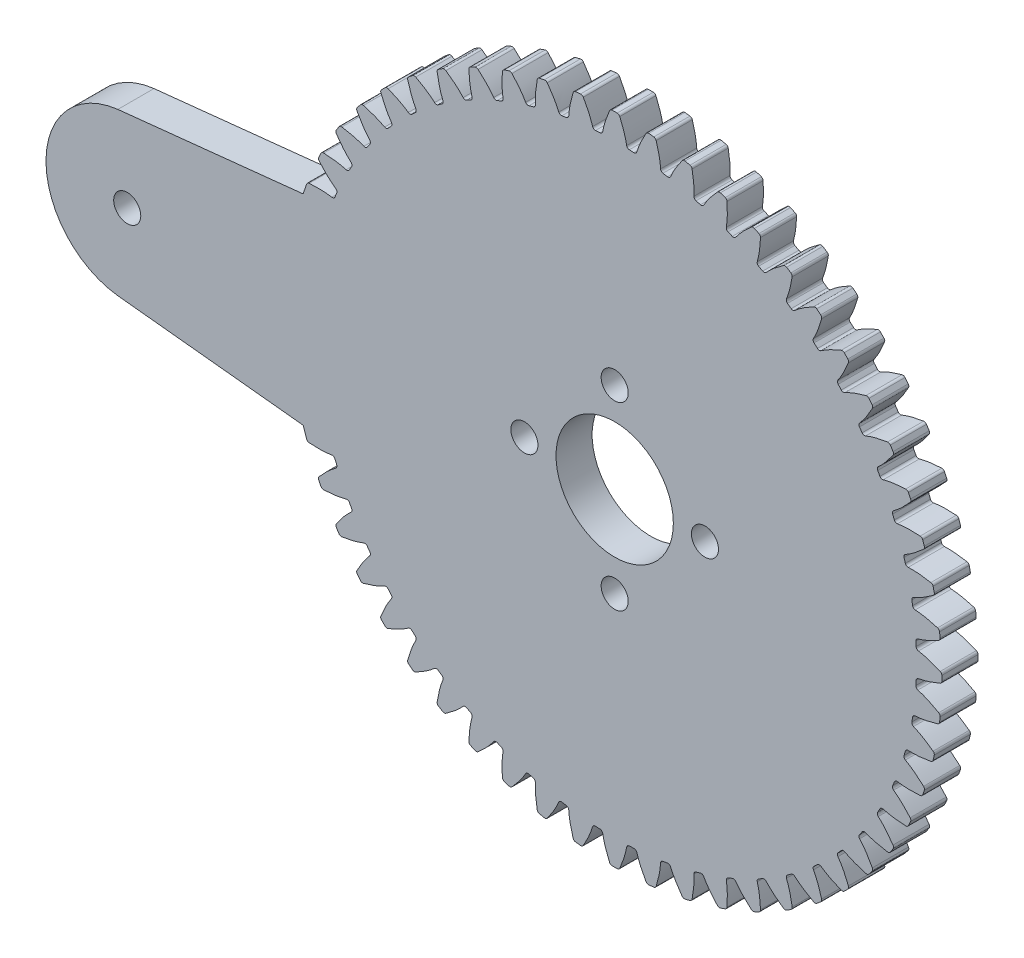
SolidWorks part; units mm, degrees
ref_plane "前视基准面" through (0, 0, 0) normal (0, 0, 1) x (1, 0, 0)
ref_plane "上视基准面" through (0, 0, 0) normal (0, 1, 0) x (1, 0, 0)
ref_plane "右视基准面" through (0, 0, 0) normal (1, 0, 0) x (0, 0, -1)
sketch "草图1" plane through (0, 0, 0) normal (0, 0, 1) x (1, 0, 0)
  line B0 (-34.5094, 11.0978) -> (-55.0401, 8.9397)
  line B1 (-55.0401, -8.9397) -> (-34.5094, -11.0978)
  line B2 (-62.9994, -0.1) -> (-62.9994, 0.1)
  circle B3 centre (10, 0) radius 0.925
  circle B4 centre (0, -10) radius 0.925
  circle B5 centre (0, 10) radius 0.925
  circle B6 centre (-10, 0) radius 0.925
  circle B7 centre (0, 0) radius 6.5
  arc B8 (-34.5094, -11.0978) -> (-34.1217, -12.2382) centre (0, 0) ccw
  circle B9 centre (-54, 0) radius 1.5
  arc B10 (-55.0401, 8.9397) -> (-62.9994, 0.1) centre (-54, 0) ccw
  arc B11 (-62.9994, -0.1) -> (-55.0401, -8.9397) centre (-54, 0) ccw
  arc B12 (-3.7786, 36.0525) -> (-4.3386, 35.9894) centre (0, 0) ccw
  arc B13 (-5.3496, 33.0068) -> (-5.601, 32.9651) centre (0, 0) ccw
  arc B14 (-2.4485, 33.592) -> (-2.1292, 33.3696) centre (-2.1491, 33.6815) ccw
  arc B15 (-5.3496, 33.0068) -> (-5.0878, 33.2946) centre (-5.3996, 33.3153) ccw
  arc B16 (-4.3386, 35.9894) -> (-4.6013, 35.7665) centre (-4.3012, 35.6792) ccw
  arc B17 (-3.4729, 35.8936) -> (-3.7786, 36.0525) centre (-3.746, 35.7417) ccw
  arc B18 (-1.8749, 33.3849) -> (-2.1292, 33.3696) centre (0, 0) ccw
  arc B19 (0.2818, 36.2489) -> (-0.2818, 36.2489) centre (0, 0) ccw
  arc B20 (-1.6204, 33.3982) -> (-1.8749, 33.3849) centre (0, 0) ccw
  arc B21 (1.328, 33.6549) -> (1.6204, 33.3982) centre (1.6355, 33.7103) ccw
  arc B22 (-1.6204, 33.3982) -> (-1.328, 33.6549) centre (-1.6355, 33.7103) ccw
  arc B23 (-0.2818, 36.2489) -> (-0.5677, 36.0568) centre (-0.2793, 35.9364) ccw
  arc B24 (0.5677, 36.0568) -> (0.2818, 36.2489) centre (0.2793, 35.9364) ccw
  arc B25 (1.8749, 33.3849) -> (1.6204, 33.3982) centre (0, 0) ccw
  arc B26 (4.3386, 35.9894) -> (3.7786, 36.0525) centre (0, 0) ccw
  arc B27 (2.1292, 33.3696) -> (1.8749, 33.3849) centre (0, 0) ccw
  arc B28 (5.0878, 33.2946) -> (5.3496, 33.0068) centre (5.3996, 33.3153) ccw
  arc B29 (2.1292, 33.3696) -> (2.4485, 33.592) centre (2.1491, 33.6815) ccw
  arc B30 (3.7786, 36.0525) -> (3.4729, 35.8936) centre (3.746, 35.7417) ccw
  arc B31 (4.6013, 35.7665) -> (4.3386, 35.9894) centre (4.3012, 35.6792) ccw
  arc B32 (5.601, 32.9651) -> (5.3496, 33.0068) centre (0, 0) ccw
  arc B33 (8.3409, 35.2774) -> (7.7914, 35.4028) centre (0, 0) ccw
  arc B34 (5.852, 32.9214) -> (5.601, 32.9651) centre (0, 0) ccw
  arc B35 (8.7836, 32.5156) -> (9.0116, 32.2003) centre (9.0958, 32.5012) ccw
  arc B36 (5.852, 32.9214) -> (6.1942, 33.1066) centre (5.9067, 33.2291) ccw
  arc B37 (7.7914, 35.4028) -> (7.4699, 35.2791) centre (7.7243, 35.0976) ccw
  arc B38 (8.5769, 35.0264) -> (8.3409, 35.2774) centre (8.2689, 34.9733) ccw
  arc B39 (9.2567, 32.1307) -> (9.0116, 32.2003) centre (0, 0) ccw
  arc B40 (12.2382, 34.1217) -> (11.7063, 34.3078) centre (0, 0) ccw
  arc B41 (9.5013, 32.0592) -> (9.2567, 32.1307) centre (0, 0) ccw
  arc B42 (12.369, 31.3277) -> (12.5602, 30.9888) centre (12.6776, 31.2785) ccw
  arc B43 (9.5013, 32.0592) -> (9.862, 32.2049) centre (9.5901, 32.3588) ccw
  arc B44 (11.7063, 34.3078) -> (11.3729, 34.2209) centre (11.6054, 34.012) ccw
  arc B45 (12.4447, 33.8459) -> (12.2382, 34.1217) centre (12.1327, 33.8275) ccw
  arc B46 (12.796, 30.8922) -> (12.5602, 30.9888) centre (0, 0) ccw
  arc B47 (15.9817, 32.5369) -> (15.4739, 32.7814) centre (0, 0) ccw
  arc B48 (13.031, 30.7938) -> (12.796, 30.8922) centre (0, 0) ccw
  arc B49 (15.7988, 29.7458) -> (15.9509, 29.3877) centre (16.0999, 29.6623) ccw
  arc B50 (13.031, 30.7938) -> (13.4058, 30.8982) centre (13.1528, 31.0816) ccw
  arc B51 (15.4739, 32.7814) -> (15.1329, 32.7324) centre (15.3405, 32.4988) ccw
  arc B52 (16.156, 32.2397) -> (15.9817, 32.5369) centre (15.8439, 32.2564) ccw
  arc B53 (16.1744, 29.2653) -> (15.9509, 29.3877) centre (0, 0) ccw
  arc B54 (19.5242, 30.5429) -> (19.047, 30.8427) centre (0, 0) ccw
  arc B55 (16.3969, 29.1412) -> (16.1744, 29.2653) centre (0, 0) ccw
  arc B56 (19.0299, 27.7899) -> (19.1409, 27.417) centre (19.3198, 27.6732) ccw
  arc B57 (16.3969, 29.1412) -> (16.781, 29.2029) centre (16.5501, 29.4135) ccw
  arc B58 (19.047, 30.8427) -> (18.7026, 30.8322) centre (18.8828, 30.5769) ccw
  arc B59 (19.6641, 30.2281) -> (19.5242, 30.5429) centre (19.3559, 30.2796) ccw
  arc B60 (19.3493, 27.2703) -> (19.1409, 27.417) centre (0, 0) ccw
  arc B61 (22.8211, 28.1649) -> (22.3805, 28.5162) centre (0, 0) ccw
  arc B62 (19.5566, 27.1221) -> (19.3493, 27.2703) centre (0, 0) ccw
  arc B63 (22.0218, 25.4845) -> (22.0903, 25.1015) centre (22.2968, 25.3361) ccw
  arc B64 (19.5566, 27.1221) -> (19.9452, 27.1404) centre (19.7393, 27.3756) ccw
  arc B65 (22.3805, 28.5162) -> (22.0371, 28.5443) centre (22.1876, 28.2704) ccw
  arc B66 (22.9249, 27.8363) -> (22.8211, 28.1649) centre (22.6244, 27.9221) ccw
  arc B67 (22.281, 24.9324) -> (22.0903, 25.1015) centre (0, 0) ccw
  arc B68 (25.8311, 25.4326) -> (25.4326, 25.8311) centre (0, 0) ccw
  arc B69 (22.4703, 24.7619) -> (22.281, 24.9324) centre (0, 0) ccw
  arc B70 (24.7366, 22.8586) -> (24.7619, 22.4703) centre (24.9933, 22.6803) ccw
  arc B71 (22.4703, 24.7619) -> (22.8586, 24.7366) centre (22.6803, 24.9933) ccw
  arc B72 (25.4326, 25.8311) -> (25.0945, 25.8974) centre (25.2134, 25.6084) ccw
  arc B73 (25.8974, 25.0945) -> (25.8311, 25.4326) centre (25.6084, 25.2134) ccw
  arc B74 (24.9324, 22.281) -> (24.7619, 22.4703) centre (0, 0) ccw
  arc B75 (28.5162, 22.3805) -> (28.1649, 22.8211) centre (0, 0) ccw
  arc B76 (25.1015, 22.0903) -> (24.9324, 22.281) centre (0, 0) ccw
  arc B77 (27.1404, 19.9452) -> (27.1221, 19.5566) centre (27.3756, 19.7393) ccw
  arc B78 (25.1015, 22.0903) -> (25.4845, 22.0218) centre (25.3361, 22.2968) ccw
  arc B79 (28.1649, 22.8211) -> (27.8363, 22.9249) centre (27.9221, 22.6244) ccw
  arc B80 (28.5443, 22.0371) -> (28.5162, 22.3805) centre (28.2704, 22.1876) ccw
  arc B81 (27.2703, 19.3493) -> (27.1221, 19.5566) centre (0, 0) ccw
  arc B82 (30.8427, 19.047) -> (30.5429, 19.5242) centre (0, 0) ccw
  arc B83 (27.417, 19.1409) -> (27.2703, 19.3493) centre (0, 0) ccw
  arc B84 (29.2029, 16.781) -> (29.1412, 16.3969) centre (29.4135, 16.5501) ccw
  arc B85 (27.417, 19.1409) -> (27.7899, 19.0299) centre (27.6732, 19.3198) ccw
  arc B86 (30.5429, 19.5242) -> (30.2281, 19.6641) centre (30.2796, 19.3559) ccw
  arc B87 (30.8322, 18.7026) -> (30.8427, 19.047) centre (30.5769, 18.8828) ccw
  arc B88 (29.2653, 16.1744) -> (29.1412, 16.3969) centre (0, 0) ccw
  arc B89 (32.7814, 15.4739) -> (32.5369, 15.9817) centre (0, 0) ccw
  arc B90 (29.3877, 15.9509) -> (29.2653, 16.1744) centre (0, 0) ccw
  arc B91 (30.8982, 13.4058) -> (30.7938, 13.031) centre (31.0816, 13.1528) ccw
  arc B92 (29.3877, 15.9509) -> (29.7458, 15.7988) centre (29.6623, 16.0999) ccw
  arc B93 (32.5369, 15.9817) -> (32.2397, 16.156) centre (32.2564, 15.8439) ccw
  arc B94 (32.7324, 15.1329) -> (32.7814, 15.4739) centre (32.4988, 15.3405) ccw
  arc B95 (30.8922, 12.796) -> (30.7938, 13.031) centre (0, 0) ccw
  arc B96 (34.3078, 11.7063) -> (34.1217, 12.2382) centre (0, 0) ccw
  arc B97 (30.9888, 12.5602) -> (30.8922, 12.796) centre (0, 0) ccw
  arc B98 (32.2049, 9.862) -> (32.0592, 9.5013) centre (32.3588, 9.5901) ccw
  arc B99 (30.9888, 12.5602) -> (31.3277, 12.369) centre (31.2785, 12.6776) ccw
  arc B100 (34.1217, 12.2382) -> (33.8459, 12.4447) centre (33.8275, 12.1327) ccw
  arc B101 (34.2209, 11.3729) -> (34.3078, 11.7063) centre (34.012, 11.6054) ccw
  arc B102 (32.1307, 9.2567) -> (32.0592, 9.5013) centre (0, 0) ccw
  arc B103 (35.4028, 7.7914) -> (35.2774, 8.3409) centre (0, 0) ccw
  arc B104 (32.2003, 9.0116) -> (32.1307, 9.2567) centre (0, 0) ccw
  arc B105 (33.1066, 6.1942) -> (32.9214, 5.852) centre (33.2291, 5.9067) ccw
  arc B106 (32.2003, 9.0116) -> (32.5156, 8.7836) centre (32.5012, 9.0958) ccw
  arc B107 (35.2774, 8.3409) -> (35.0264, 8.5769) centre (34.9733, 8.2689) ccw
  arc B108 (35.2791, 7.4699) -> (35.4028, 7.7914) centre (35.0976, 7.7243) ccw
  arc B109 (32.9651, 5.601) -> (32.9214, 5.852) centre (0, 0) ccw
  arc B110 (36.0525, 3.7786) -> (35.9894, 4.3386) centre (0, 0) ccw
  arc B111 (33.0068, 5.3496) -> (32.9651, 5.601) centre (0, 0) ccw
  arc B112 (33.592, 2.4485) -> (33.3696, 2.1292) centre (33.6815, 2.1491) ccw
  arc B113 (33.0068, 5.3496) -> (33.2946, 5.0878) centre (33.3153, 5.3996) ccw
  arc B114 (35.9894, 4.3386) -> (35.7665, 4.6013) centre (35.6792, 4.3012) ccw
  arc B115 (35.8936, 3.4729) -> (36.0525, 3.7786) centre (35.7417, 3.746) ccw
  arc B116 (33.3849, 1.8749) -> (33.3696, 2.1292) centre (0, 0) ccw
  arc B117 (36.2489, -0.2818) -> (36.2489, 0.2818) centre (0, 0) ccw
  arc B118 (33.3982, 1.6204) -> (33.3849, 1.8749) centre (0, 0) ccw
  arc B119 (33.6549, -1.328) -> (33.3982, -1.6204) centre (33.7103, -1.6355) ccw
  arc B120 (33.3982, 1.6204) -> (33.6549, 1.328) centre (33.7103, 1.6355) ccw
  arc B121 (36.2489, 0.2818) -> (36.0568, 0.5677) centre (35.9364, 0.2793) ccw
  arc B122 (36.0568, -0.5677) -> (36.2489, -0.2818) centre (35.9364, -0.2793) ccw
  arc B123 (33.3849, -1.8749) -> (33.3982, -1.6204) centre (0, 0) ccw
  arc B124 (35.9894, -4.3386) -> (36.0525, -3.7786) centre (0, 0) ccw
  arc B125 (33.3696, -2.1292) -> (33.3849, -1.8749) centre (0, 0) ccw
  arc B126 (33.2946, -5.0878) -> (33.0068, -5.3496) centre (33.3153, -5.3996) ccw
  arc B127 (33.3696, -2.1292) -> (33.592, -2.4485) centre (33.6815, -2.1491) ccw
  arc B128 (36.0525, -3.7786) -> (35.8936, -3.4729) centre (35.7417, -3.746) ccw
  arc B129 (35.7665, -4.6013) -> (35.9894, -4.3386) centre (35.6792, -4.3012) ccw
  arc B130 (32.9651, -5.601) -> (33.0068, -5.3496) centre (0, 0) ccw
  arc B131 (35.2774, -8.3409) -> (35.4028, -7.7914) centre (0, 0) ccw
  arc B132 (32.9214, -5.852) -> (32.9651, -5.601) centre (0, 0) ccw
  arc B133 (32.5156, -8.7836) -> (32.2003, -9.0116) centre (32.5012, -9.0958) ccw
  arc B134 (32.9214, -5.852) -> (33.1066, -6.1942) centre (33.2291, -5.9067) ccw
  arc B135 (35.4028, -7.7914) -> (35.2791, -7.4699) centre (35.0976, -7.7243) ccw
  arc B136 (35.0264, -8.5769) -> (35.2774, -8.3409) centre (34.9733, -8.2689) ccw
  arc B137 (32.1307, -9.2567) -> (32.2003, -9.0116) centre (0, 0) ccw
  arc B138 (34.1217, -12.2382) -> (34.3078, -11.7063) centre (0, 0) ccw
  arc B139 (32.0592, -9.5013) -> (32.1307, -9.2567) centre (0, 0) ccw
  arc B140 (31.3277, -12.369) -> (30.9888, -12.5602) centre (31.2785, -12.6776) ccw
  arc B141 (32.0592, -9.5013) -> (32.2049, -9.862) centre (32.3588, -9.5901) ccw
  arc B142 (34.3078, -11.7063) -> (34.2209, -11.3729) centre (34.012, -11.6054) ccw
  arc B143 (33.8459, -12.4447) -> (34.1217, -12.2382) centre (33.8275, -12.1327) ccw
  arc B144 (30.8922, -12.796) -> (30.9888, -12.5602) centre (0, 0) ccw
  arc B145 (32.5369, -15.9817) -> (32.7814, -15.4739) centre (0, 0) ccw
  arc B146 (30.7938, -13.031) -> (30.8922, -12.796) centre (0, 0) ccw
  arc B147 (29.7458, -15.7988) -> (29.3877, -15.9509) centre (29.6623, -16.0999) ccw
  arc B148 (30.7938, -13.031) -> (30.8982, -13.4058) centre (31.0816, -13.1528) ccw
  arc B149 (32.7814, -15.4739) -> (32.7324, -15.1329) centre (32.4988, -15.3405) ccw
  arc B150 (32.2397, -16.156) -> (32.5369, -15.9817) centre (32.2564, -15.8439) ccw
  arc B151 (29.2653, -16.1744) -> (29.3877, -15.9509) centre (0, 0) ccw
  arc B152 (30.5429, -19.5242) -> (30.8427, -19.047) centre (0, 0) ccw
  arc B153 (29.1412, -16.3969) -> (29.2653, -16.1744) centre (0, 0) ccw
  arc B154 (27.7899, -19.0299) -> (27.417, -19.1409) centre (27.6732, -19.3198) ccw
  arc B155 (29.1412, -16.3969) -> (29.2029, -16.781) centre (29.4135, -16.5501) ccw
  arc B156 (30.8427, -19.047) -> (30.8322, -18.7026) centre (30.5769, -18.8828) ccw
  arc B157 (30.2281, -19.6641) -> (30.5429, -19.5242) centre (30.2796, -19.3559) ccw
  arc B158 (27.2703, -19.3493) -> (27.417, -19.1409) centre (0, 0) ccw
  arc B159 (28.1649, -22.8211) -> (28.5162, -22.3805) centre (0, 0) ccw
  arc B160 (27.1221, -19.5566) -> (27.2703, -19.3493) centre (0, 0) ccw
  arc B161 (25.4845, -22.0218) -> (25.1015, -22.0903) centre (25.3361, -22.2968) ccw
  arc B162 (27.1221, -19.5566) -> (27.1404, -19.9452) centre (27.3756, -19.7393) ccw
  arc B163 (28.5162, -22.3805) -> (28.5443, -22.0371) centre (28.2704, -22.1876) ccw
  arc B164 (27.8363, -22.9249) -> (28.1649, -22.8211) centre (27.9221, -22.6244) ccw
  arc B165 (24.9324, -22.281) -> (25.1015, -22.0903) centre (0, 0) ccw
  arc B166 (25.4326, -25.8311) -> (25.8311, -25.4326) centre (0, 0) ccw
  arc B167 (24.7619, -22.4703) -> (24.9324, -22.281) centre (0, 0) ccw
  arc B168 (22.8586, -24.7366) -> (22.4703, -24.7619) centre (22.6803, -24.9933) ccw
  arc B169 (24.7619, -22.4703) -> (24.7366, -22.8586) centre (24.9933, -22.6803) ccw
  arc B170 (25.8311, -25.4326) -> (25.8974, -25.0945) centre (25.6084, -25.2134) ccw
  arc B171 (25.0945, -25.8974) -> (25.4326, -25.8311) centre (25.2134, -25.6084) ccw
  arc B172 (22.281, -24.9324) -> (22.4703, -24.7619) centre (0, 0) ccw
  arc B173 (22.3805, -28.5162) -> (22.8211, -28.1649) centre (0, 0) ccw
  arc B174 (22.0903, -25.1015) -> (22.281, -24.9324) centre (0, 0) ccw
  arc B175 (19.9452, -27.1404) -> (19.5566, -27.1221) centre (19.7393, -27.3756) ccw
  arc B176 (22.0903, -25.1015) -> (22.0218, -25.4845) centre (22.2968, -25.3361) ccw
  arc B177 (22.8211, -28.1649) -> (22.9249, -27.8363) centre (22.6244, -27.9221) ccw
  arc B178 (22.0371, -28.5443) -> (22.3805, -28.5162) centre (22.1876, -28.2704) ccw
  arc B179 (19.3493, -27.2703) -> (19.5566, -27.1221) centre (0, 0) ccw
  arc B180 (19.047, -30.8427) -> (19.5242, -30.5429) centre (0, 0) ccw
  arc B181 (19.1409, -27.417) -> (19.3493, -27.2703) centre (0, 0) ccw
  arc B182 (16.781, -29.2029) -> (16.3969, -29.1412) centre (16.5501, -29.4135) ccw
  arc B183 (19.1409, -27.417) -> (19.0299, -27.7899) centre (19.3198, -27.6732) ccw
  arc B184 (19.5242, -30.5429) -> (19.6641, -30.2281) centre (19.3559, -30.2796) ccw
  arc B185 (18.7026, -30.8322) -> (19.047, -30.8427) centre (18.8828, -30.5769) ccw
  arc B186 (16.1744, -29.2653) -> (16.3969, -29.1412) centre (0, 0) ccw
  arc B187 (15.4739, -32.7814) -> (15.9817, -32.5369) centre (0, 0) ccw
  arc B188 (15.9509, -29.3877) -> (16.1744, -29.2653) centre (0, 0) ccw
  arc B189 (13.4058, -30.8982) -> (13.031, -30.7938) centre (13.1528, -31.0816) ccw
  arc B190 (15.9509, -29.3877) -> (15.7988, -29.7458) centre (16.0999, -29.6623) ccw
  arc B191 (15.9817, -32.5369) -> (16.156, -32.2397) centre (15.8439, -32.2564) ccw
  arc B192 (15.1329, -32.7324) -> (15.4739, -32.7814) centre (15.3405, -32.4988) ccw
  arc B193 (12.796, -30.8922) -> (13.031, -30.7938) centre (0, 0) ccw
  arc B194 (11.7063, -34.3078) -> (12.2382, -34.1217) centre (0, 0) ccw
  arc B195 (12.5602, -30.9888) -> (12.796, -30.8922) centre (0, 0) ccw
  arc B196 (9.862, -32.2049) -> (9.5013, -32.0592) centre (9.5901, -32.3588) ccw
  arc B197 (12.5602, -30.9888) -> (12.369, -31.3277) centre (12.6776, -31.2785) ccw
  arc B198 (12.2382, -34.1217) -> (12.4447, -33.8459) centre (12.1327, -33.8275) ccw
  arc B199 (11.3729, -34.2209) -> (11.7063, -34.3078) centre (11.6054, -34.012) ccw
  arc B200 (9.2567, -32.1307) -> (9.5013, -32.0592) centre (0, 0) ccw
  arc B201 (7.7914, -35.4028) -> (8.3409, -35.2774) centre (0, 0) ccw
  arc B202 (9.0116, -32.2003) -> (9.2567, -32.1307) centre (0, 0) ccw
  arc B203 (6.1942, -33.1066) -> (5.852, -32.9214) centre (5.9067, -33.2291) ccw
  arc B204 (9.0116, -32.2003) -> (8.7836, -32.5156) centre (9.0958, -32.5012) ccw
  arc B205 (8.3409, -35.2774) -> (8.5769, -35.0264) centre (8.2689, -34.9733) ccw
  arc B206 (7.4699, -35.2791) -> (7.7914, -35.4028) centre (7.7243, -35.0976) ccw
  arc B207 (5.601, -32.9651) -> (5.852, -32.9214) centre (0, 0) ccw
  arc B208 (3.7786, -36.0525) -> (4.3386, -35.9894) centre (0, 0) ccw
  arc B209 (5.3496, -33.0068) -> (5.601, -32.9651) centre (0, 0) ccw
  arc B210 (2.4485, -33.592) -> (2.1292, -33.3696) centre (2.1491, -33.6815) ccw
  arc B211 (5.3496, -33.0068) -> (5.0878, -33.2946) centre (5.3996, -33.3153) ccw
  arc B212 (4.3386, -35.9894) -> (4.6013, -35.7665) centre (4.3012, -35.6792) ccw
  arc B213 (3.4729, -35.8936) -> (3.7786, -36.0525) centre (3.746, -35.7417) ccw
  arc B214 (1.8749, -33.3849) -> (2.1292, -33.3696) centre (0, 0) ccw
  arc B215 (-0.2818, -36.2489) -> (0.2818, -36.2489) centre (0, 0) ccw
  arc B216 (1.6204, -33.3982) -> (1.8749, -33.3849) centre (0, 0) ccw
  arc B217 (-1.328, -33.6549) -> (-1.6204, -33.3982) centre (-1.6355, -33.7103) ccw
  arc B218 (1.6204, -33.3982) -> (1.328, -33.6549) centre (1.6355, -33.7103) ccw
  arc B219 (0.2818, -36.2489) -> (0.5677, -36.0568) centre (0.2793, -35.9364) ccw
  arc B220 (-0.5677, -36.0568) -> (-0.2818, -36.2489) centre (-0.2793, -35.9364) ccw
  arc B221 (-1.8749, -33.3849) -> (-1.6204, -33.3982) centre (0, 0) ccw
  arc B222 (-4.3386, -35.9894) -> (-3.7786, -36.0525) centre (0, 0) ccw
  arc B223 (-2.1292, -33.3696) -> (-1.8749, -33.3849) centre (0, 0) ccw
  arc B224 (-5.0878, -33.2946) -> (-5.3496, -33.0068) centre (-5.3996, -33.3153) ccw
  arc B225 (-2.1292, -33.3696) -> (-2.4485, -33.592) centre (-2.1491, -33.6815) ccw
  arc B226 (-3.7786, -36.0525) -> (-3.4729, -35.8936) centre (-3.746, -35.7417) ccw
  arc B227 (-4.6013, -35.7665) -> (-4.3386, -35.9894) centre (-4.3012, -35.6792) ccw
  arc B228 (-5.601, -32.9651) -> (-5.3496, -33.0068) centre (0, 0) ccw
  arc B229 (-8.3409, -35.2774) -> (-7.7914, -35.4028) centre (0, 0) ccw
  arc B230 (-5.852, -32.9214) -> (-5.601, -32.9651) centre (0, 0) ccw
  arc B231 (-8.7836, -32.5156) -> (-9.0116, -32.2003) centre (-9.0958, -32.5012) ccw
  arc B232 (-5.852, -32.9214) -> (-6.1942, -33.1066) centre (-5.9067, -33.2291) ccw
  arc B233 (-7.7914, -35.4028) -> (-7.4699, -35.2791) centre (-7.7243, -35.0976) ccw
  arc B234 (-8.5769, -35.0264) -> (-8.3409, -35.2774) centre (-8.2689, -34.9733) ccw
  arc B235 (-9.2567, -32.1307) -> (-9.0116, -32.2003) centre (0, 0) ccw
  arc B236 (-12.2382, -34.1217) -> (-11.7063, -34.3078) centre (0, 0) ccw
  arc B237 (-9.5013, -32.0592) -> (-9.2567, -32.1307) centre (0, 0) ccw
  arc B238 (-12.369, -31.3277) -> (-12.5602, -30.9888) centre (-12.6776, -31.2785) ccw
  arc B239 (-9.5013, -32.0592) -> (-9.862, -32.2049) centre (-9.5901, -32.3588) ccw
  arc B240 (-11.7063, -34.3078) -> (-11.3729, -34.2209) centre (-11.6054, -34.012) ccw
  arc B241 (-12.4447, -33.8459) -> (-12.2382, -34.1217) centre (-12.1327, -33.8275) ccw
  arc B242 (-12.796, -30.8922) -> (-12.5602, -30.9888) centre (0, 0) ccw
  arc B243 (-15.9817, -32.5369) -> (-15.4739, -32.7814) centre (0, 0) ccw
  arc B244 (-13.031, -30.7938) -> (-12.796, -30.8922) centre (0, 0) ccw
  arc B245 (-15.7988, -29.7458) -> (-15.9509, -29.3877) centre (-16.0999, -29.6623) ccw
  arc B246 (-13.031, -30.7938) -> (-13.4058, -30.8982) centre (-13.1528, -31.0816) ccw
  arc B247 (-15.4739, -32.7814) -> (-15.1329, -32.7324) centre (-15.3405, -32.4988) ccw
  arc B248 (-16.156, -32.2397) -> (-15.9817, -32.5369) centre (-15.8439, -32.2564) ccw
  arc B249 (-16.1744, -29.2653) -> (-15.9509, -29.3877) centre (0, 0) ccw
  arc B250 (-19.5242, -30.5429) -> (-19.047, -30.8427) centre (0, 0) ccw
  arc B251 (-16.3969, -29.1412) -> (-16.1744, -29.2653) centre (0, 0) ccw
  arc B252 (-19.0299, -27.7899) -> (-19.1409, -27.417) centre (-19.3198, -27.6732) ccw
  arc B253 (-16.3969, -29.1412) -> (-16.781, -29.2029) centre (-16.5501, -29.4135) ccw
  arc B254 (-19.047, -30.8427) -> (-18.7026, -30.8322) centre (-18.8828, -30.5769) ccw
  arc B255 (-19.6641, -30.2281) -> (-19.5242, -30.5429) centre (-19.3559, -30.2796) ccw
  arc B256 (-19.3493, -27.2703) -> (-19.1409, -27.417) centre (0, 0) ccw
  arc B257 (-22.8211, -28.1649) -> (-22.3805, -28.5162) centre (0, 0) ccw
  arc B258 (-19.5566, -27.1221) -> (-19.3493, -27.2703) centre (0, 0) ccw
  arc B259 (-22.0218, -25.4845) -> (-22.0903, -25.1015) centre (-22.2968, -25.3361) ccw
  arc B260 (-19.5566, -27.1221) -> (-19.9452, -27.1404) centre (-19.7393, -27.3756) ccw
  arc B261 (-22.3805, -28.5162) -> (-22.0371, -28.5443) centre (-22.1876, -28.2704) ccw
  arc B262 (-22.9249, -27.8363) -> (-22.8211, -28.1649) centre (-22.6244, -27.9221) ccw
  arc B263 (-22.281, -24.9324) -> (-22.0903, -25.1015) centre (0, 0) ccw
  arc B264 (-25.8311, -25.4326) -> (-25.4326, -25.8311) centre (0, 0) ccw
  arc B265 (-22.4703, -24.7619) -> (-22.281, -24.9324) centre (0, 0) ccw
  arc B266 (-24.7366, -22.8586) -> (-24.7619, -22.4703) centre (-24.9933, -22.6803) ccw
  arc B267 (-22.4703, -24.7619) -> (-22.8586, -24.7366) centre (-22.6803, -24.9933) ccw
  arc B268 (-25.4326, -25.8311) -> (-25.0945, -25.8974) centre (-25.2134, -25.6084) ccw
  arc B269 (-25.8974, -25.0945) -> (-25.8311, -25.4326) centre (-25.6084, -25.2134) ccw
  arc B270 (-24.9324, -22.281) -> (-24.7619, -22.4703) centre (0, 0) ccw
  arc B271 (-28.5162, -22.3805) -> (-28.1649, -22.8211) centre (0, 0) ccw
  arc B272 (-25.1015, -22.0903) -> (-24.9324, -22.281) centre (0, 0) ccw
  arc B273 (-27.1404, -19.9452) -> (-27.1221, -19.5566) centre (-27.3756, -19.7393) ccw
  arc B274 (-25.1015, -22.0903) -> (-25.4845, -22.0218) centre (-25.3361, -22.2968) ccw
  arc B275 (-28.1649, -22.8211) -> (-27.8363, -22.9249) centre (-27.9221, -22.6244) ccw
  arc B276 (-28.5443, -22.0371) -> (-28.5162, -22.3805) centre (-28.2704, -22.1876) ccw
  arc B277 (-27.2703, -19.3493) -> (-27.1221, -19.5566) centre (0, 0) ccw
  arc B278 (-30.8427, -19.047) -> (-30.5429, -19.5242) centre (0, 0) ccw
  arc B279 (-27.417, -19.1409) -> (-27.2703, -19.3493) centre (0, 0) ccw
  arc B280 (-29.2029, -16.781) -> (-29.1412, -16.3969) centre (-29.4135, -16.5501) ccw
  arc B281 (-27.417, -19.1409) -> (-27.7899, -19.0299) centre (-27.6732, -19.3198) ccw
  arc B282 (-30.5429, -19.5242) -> (-30.2281, -19.6641) centre (-30.2796, -19.3559) ccw
  arc B283 (-30.8322, -18.7026) -> (-30.8427, -19.047) centre (-30.5769, -18.8828) ccw
  arc B284 (-29.2653, -16.1744) -> (-29.1412, -16.3969) centre (0, 0) ccw
  arc B285 (-32.7814, -15.4739) -> (-32.5369, -15.9817) centre (0, 0) ccw
  arc B286 (-29.3877, -15.9509) -> (-29.2653, -16.1744) centre (0, 0) ccw
  arc B287 (-30.8982, -13.4058) -> (-30.7938, -13.031) centre (-31.0816, -13.1528) ccw
  arc B288 (-29.3877, -15.9509) -> (-29.7458, -15.7988) centre (-29.6623, -16.0999) ccw
  arc B289 (-32.5369, -15.9817) -> (-32.2397, -16.156) centre (-32.2564, -15.8439) ccw
  arc B290 (-32.7324, -15.1329) -> (-32.7814, -15.4739) centre (-32.4988, -15.3405) ccw
  arc B291 (-30.8922, -12.796) -> (-30.7938, -13.031) centre (0, 0) ccw
  arc B292 (-34.3078, -11.7063) -> (-34.1217, -12.2382) centre (0, 0) ccw
  arc B293 (-30.9888, -12.5602) -> (-30.8922, -12.796) centre (0, 0) ccw
  arc B294 (-30.9888, -12.5602) -> (-31.3277, -12.369) centre (-31.2785, -12.6776) ccw
  arc B295 (-34.1217, -12.2382) -> (-33.8459, -12.4447) centre (-33.8275, -12.1327) ccw
  arc B296 (-34.1217, 12.2382) -> (-34.5094, 11.0978) centre (0, 0) ccw
  arc B297 (-31.3277, 12.369) -> (-30.9888, 12.5602) centre (-31.2785, 12.6776) ccw
  arc B298 (-33.8459, 12.4447) -> (-34.1217, 12.2382) centre (-33.8275, 12.1327) ccw
  arc B299 (-30.8922, 12.796) -> (-30.9888, 12.5602) centre (0, 0) ccw
  arc B300 (-32.5369, 15.9817) -> (-32.7814, 15.4739) centre (0, 0) ccw
  arc B301 (-30.7938, 13.031) -> (-30.8922, 12.796) centre (0, 0) ccw
  arc B302 (-29.7458, 15.7988) -> (-29.3877, 15.9509) centre (-29.6623, 16.0999) ccw
  arc B303 (-30.7938, 13.031) -> (-30.8982, 13.4058) centre (-31.0816, 13.1528) ccw
  arc B304 (-32.7814, 15.4739) -> (-32.7324, 15.1329) centre (-32.4988, 15.3405) ccw
  arc B305 (-32.2397, 16.156) -> (-32.5369, 15.9817) centre (-32.2564, 15.8439) ccw
  arc B306 (-29.2653, 16.1744) -> (-29.3877, 15.9509) centre (0, 0) ccw
  arc B307 (-30.5429, 19.5242) -> (-30.8427, 19.047) centre (0, 0) ccw
  arc B308 (-29.1412, 16.3969) -> (-29.2653, 16.1744) centre (0, 0) ccw
  arc B309 (-27.7899, 19.0299) -> (-27.417, 19.1409) centre (-27.6732, 19.3198) ccw
  arc B310 (-29.1412, 16.3969) -> (-29.2029, 16.781) centre (-29.4135, 16.5501) ccw
  arc B311 (-30.8427, 19.047) -> (-30.8322, 18.7026) centre (-30.5769, 18.8828) ccw
  arc B312 (-30.2281, 19.6641) -> (-30.5429, 19.5242) centre (-30.2796, 19.3559) ccw
  arc B313 (-27.2703, 19.3493) -> (-27.417, 19.1409) centre (0, 0) ccw
  arc B314 (-28.1649, 22.8211) -> (-28.5162, 22.3805) centre (0, 0) ccw
  arc B315 (-27.1221, 19.5566) -> (-27.2703, 19.3493) centre (0, 0) ccw
  arc B316 (-25.4845, 22.0218) -> (-25.1015, 22.0903) centre (-25.3361, 22.2968) ccw
  arc B317 (-27.1221, 19.5566) -> (-27.1404, 19.9452) centre (-27.3756, 19.7393) ccw
  arc B318 (-28.5162, 22.3805) -> (-28.5443, 22.0371) centre (-28.2704, 22.1876) ccw
  arc B319 (-27.8363, 22.9249) -> (-28.1649, 22.8211) centre (-27.9221, 22.6244) ccw
  arc B320 (-24.9324, 22.281) -> (-25.1015, 22.0903) centre (0, 0) ccw
  arc B321 (-25.4326, 25.8311) -> (-25.8311, 25.4326) centre (0, 0) ccw
  arc B322 (-24.7619, 22.4703) -> (-24.9324, 22.281) centre (0, 0) ccw
  arc B323 (-22.8586, 24.7366) -> (-22.4703, 24.7619) centre (-22.6803, 24.9933) ccw
  arc B324 (-24.7619, 22.4703) -> (-24.7366, 22.8586) centre (-24.9933, 22.6803) ccw
  arc B325 (-25.8311, 25.4326) -> (-25.8974, 25.0945) centre (-25.6084, 25.2134) ccw
  arc B326 (-25.0945, 25.8974) -> (-25.4326, 25.8311) centre (-25.2134, 25.6084) ccw
  arc B327 (-22.281, 24.9324) -> (-22.4703, 24.7619) centre (0, 0) ccw
  arc B328 (-22.3805, 28.5162) -> (-22.8211, 28.1649) centre (0, 0) ccw
  arc B329 (-22.0903, 25.1015) -> (-22.281, 24.9324) centre (0, 0) ccw
  arc B330 (-19.9452, 27.1404) -> (-19.5566, 27.1221) centre (-19.7393, 27.3756) ccw
  arc B331 (-22.0903, 25.1015) -> (-22.0218, 25.4845) centre (-22.2968, 25.3361) ccw
  arc B332 (-22.8211, 28.1649) -> (-22.9249, 27.8363) centre (-22.6244, 27.9221) ccw
  arc B333 (-22.0371, 28.5443) -> (-22.3805, 28.5162) centre (-22.1876, 28.2704) ccw
  arc B334 (-19.3493, 27.2703) -> (-19.5566, 27.1221) centre (0, 0) ccw
  arc B335 (-19.047, 30.8427) -> (-19.5242, 30.5429) centre (0, 0) ccw
  arc B336 (-19.1409, 27.417) -> (-19.3493, 27.2703) centre (0, 0) ccw
  arc B337 (-16.781, 29.2029) -> (-16.3969, 29.1412) centre (-16.5501, 29.4135) ccw
  arc B338 (-19.1409, 27.417) -> (-19.0299, 27.7899) centre (-19.3198, 27.6732) ccw
  arc B339 (-19.5242, 30.5429) -> (-19.6641, 30.2281) centre (-19.3559, 30.2796) ccw
  arc B340 (-18.7026, 30.8322) -> (-19.047, 30.8427) centre (-18.8828, 30.5769) ccw
  arc B341 (-16.1744, 29.2653) -> (-16.3969, 29.1412) centre (0, 0) ccw
  arc B342 (-15.4739, 32.7814) -> (-15.9817, 32.5369) centre (0, 0) ccw
  arc B343 (-15.9509, 29.3877) -> (-16.1744, 29.2653) centre (0, 0) ccw
  arc B344 (-13.4058, 30.8982) -> (-13.031, 30.7938) centre (-13.1528, 31.0816) ccw
  arc B345 (-15.9509, 29.3877) -> (-15.7988, 29.7458) centre (-16.0999, 29.6623) ccw
  arc B346 (-15.9817, 32.5369) -> (-16.156, 32.2397) centre (-15.8439, 32.2564) ccw
  arc B347 (-15.1329, 32.7324) -> (-15.4739, 32.7814) centre (-15.3405, 32.4988) ccw
  arc B348 (-12.796, 30.8922) -> (-13.031, 30.7938) centre (0, 0) ccw
  arc B349 (-11.7063, 34.3078) -> (-12.2382, 34.1217) centre (0, 0) ccw
  arc B350 (-12.5602, 30.9888) -> (-12.796, 30.8922) centre (0, 0) ccw
  arc B351 (-9.862, 32.2049) -> (-9.5013, 32.0592) centre (-9.5901, 32.3588) ccw
  arc B352 (-12.5602, 30.9888) -> (-12.369, 31.3277) centre (-12.6776, 31.2785) ccw
  arc B353 (-12.2382, 34.1217) -> (-12.4447, 33.8459) centre (-12.1327, 33.8275) ccw
  arc B354 (-11.3729, 34.2209) -> (-11.7063, 34.3078) centre (-11.6054, 34.012) ccw
  arc B355 (-9.2567, 32.1307) -> (-9.5013, 32.0592) centre (0, 0) ccw
  arc B356 (-5.601, 32.9651) -> (-5.852, 32.9214) centre (0, 0) ccw
  arc B357 (-7.4699, 35.2791) -> (-7.7914, 35.4028) centre (-7.7243, 35.0976) ccw
  arc B358 (-8.3409, 35.2774) -> (-8.5769, 35.0264) centre (-8.2689, 34.9733) ccw
  arc B359 (-9.0116, 32.2003) -> (-8.7836, 32.5156) centre (-9.0958, 32.5012) ccw
  arc B360 (-6.1942, 33.1066) -> (-5.852, 32.9214) centre (-5.9067, 33.2291) ccw
  arc B361 (-9.0116, 32.2003) -> (-9.2567, 32.1307) centre (0, 0) ccw
  arc B362 (-7.7914, 35.4028) -> (-8.3409, 35.2774) centre (0, 0) ccw
  spline B363 degree 3 poles (-4.6013, 35.7665) (-4.7005, 35.4253) (-4.8862, 34.766) (-5.031, 33.9352) (-5.0774, 33.451) (-5.0878, 33.2946) knots 0.205794 0.205794 0.205794 0.205794 1.271237 2.259978 2.73007 2.73007 2.73007 2.73007
  spline B364 degree 3 poles (-3.4729, 35.8936) (-3.3002, 35.583) (-2.9725, 34.9816) (-2.6465, 34.2038) (-2.4934, 33.7421) (-2.4485, 33.592) knots 0.205794 0.205794 0.205794 0.205794 1.271237 2.259978 2.73007 2.73007 2.73007 2.73007
  spline B365 degree 3 poles (-0.5677, 36.0568) (-0.7046, 35.7288) (-0.9629, 35.0945) (-1.1998, 34.2851) (-1.3002, 33.8091) (-1.328, 33.6549) knots 0.205794 0.205794 0.205794 0.205794 1.271237 2.259978 2.73007 2.73007 2.73007 2.73007
  spline B366 degree 3 poles (0.5677, 36.0568) (0.7046, 35.7288) (0.9629, 35.0945) (1.1998, 34.2851) (1.3002, 33.8091) (1.328, 33.6549) knots 0.205794 0.205794 0.205794 0.205794 1.271237 2.259978 2.73007 2.73007 2.73007 2.73007
  spline B367 degree 3 poles (3.4729, 35.8936) (3.3002, 35.583) (2.9725, 34.9816) (2.6465, 34.2038) (2.4934, 33.7421) (2.4485, 33.592) knots 0.205794 0.205794 0.205794 0.205794 1.271237 2.259978 2.73007 2.73007 2.73007 2.73007
  spline B368 degree 3 poles (4.6013, 35.7665) (4.7005, 35.4253) (4.8862, 34.766) (5.031, 33.9352) (5.0774, 33.451) (5.0878, 33.2946) knots 0.205794 0.205794 0.205794 0.205794 1.271237 2.259978 2.73007 2.73007 2.73007 2.73007
  spline B369 degree 3 poles (7.4699, 35.2791) (7.2635, 34.9898) (6.8705, 34.4288) (6.4594, 33.6925) (6.2557, 33.2508) (6.1942, 33.1066) knots 0.205794 0.205794 0.205794 0.205794 1.271237 2.259978 2.73007 2.73007 2.73007 2.73007
  spline B370 degree 3 poles (8.5769, 35.0264) (8.6373, 34.6762) (8.748, 34.0003) (8.7989, 33.1585) (8.7908, 32.6722) (8.7836, 32.5156) knots 0.205794 0.205794 0.205794 0.205794 1.271237 2.259978 2.73007 2.73007 2.73007 2.73007
  spline B371 degree 3 poles (11.3729, 34.2209) (11.1354, 33.9565) (10.6821, 33.4431) (10.1912, 32.7574) (9.9392, 32.3413) (9.862, 32.2049) knots 0.205794 0.205794 0.205794 0.205794 1.271237 2.259978 2.73007 2.73007 2.73007 2.73007
  spline B372 degree 3 poles (12.4447, 33.8459) (12.4655, 33.4911) (12.4999, 32.8071) (12.4561, 31.9648) (12.3937, 31.4825) (12.369, 31.3277) knots 0.205794 0.205794 0.205794 0.205794 1.271237 2.259978 2.73007 2.73007 2.73007 2.73007
  spline B373 degree 3 poles (15.1329, 32.7324) (14.8673, 32.4963) (14.3594, 32.0368) (13.7948, 31.4104) (13.4978, 31.0251) (13.4058, 30.8982) knots 0.205794 0.205794 0.205794 0.205794 1.271237 2.259978 2.73007 2.73007 2.73007 2.73007
  spline B374 degree 3 poles (16.156, 32.2397) (16.137, 31.8848) (16.0945, 31.2012) (15.9567, 30.3692) (15.8407, 29.8969) (15.7988, 29.7458) knots 0.205794 0.205794 0.205794 0.205794 1.271237 2.259978 2.73007 2.73007 2.73007 2.73007
  spline B375 degree 3 poles (18.7026, 30.8322) (18.4123, 30.6273) (17.8561, 30.2276) (17.2249, 29.6683) (16.8867, 29.3188) (16.781, 29.2029) knots 0.205794 0.205794 0.205794 0.205794 1.271237 2.259978 2.73007 2.73007 2.73007 2.73007
  spline B376 degree 3 poles (19.6641, 30.2281) (19.6055, 29.8776) (19.4867, 29.203) (19.2567, 28.3917) (19.0884, 27.9353) (19.0299, 27.7899) knots 0.205794 0.205794 0.205794 0.205794 1.271237 2.259978 2.73007 2.73007 2.73007 2.73007
  spline B377 degree 3 poles (22.0371, 28.5443) (21.7257, 28.3732) (21.1282, 28.0383) (20.4384, 27.5532) (20.0631, 27.2437) (19.9452, 27.1404) knots 0.205794 0.205794 0.205794 0.205794 1.271237 2.259978 2.73007 2.73007 2.73007 2.73007
  spline B378 degree 3 poles (22.9249, 27.8363) (22.8274, 27.4946) (22.6339, 26.8376) (22.3144, 26.0571) (22.0962, 25.6224) (22.0218, 25.4845) knots 0.205794 0.205794 0.205794 0.205794 1.271237 2.259978 2.73007 2.73007 2.73007 2.73007
  spline B379 degree 3 poles (25.0945, 25.8974) (24.7659, 25.7623) (24.1346, 25.4964) (23.3948, 25.0916) (22.9873, 24.826) (22.8586, 24.7366) knots 0.205794 0.205794 0.205794 0.205794 1.271237 2.259978 2.73007 2.73007 2.73007 2.73007
  spline B380 degree 3 poles (25.8974, 25.0945) (25.7623, 24.7659) (25.4964, 24.1346) (25.0916, 23.3948) (24.826, 22.9873) (24.7366, 22.8586) knots 0.205794 0.205794 0.205794 0.205794 1.271237 2.259978 2.73007 2.73007 2.73007 2.73007
  spline B381 degree 3 poles (27.8363, 22.9249) (27.4946, 22.8274) (26.8376, 22.6339) (26.0571, 22.3144) (25.6224, 22.0962) (25.4845, 22.0218) knots 0.205794 0.205794 0.205794 0.205794 1.271237 2.259978 2.73007 2.73007 2.73007 2.73007
  spline B382 degree 3 poles (28.5443, 22.0371) (28.3732, 21.7257) (28.0383, 21.1282) (27.5532, 20.4384) (27.2437, 20.0631) (27.1404, 19.9452) knots 0.205794 0.205794 0.205794 0.205794 1.271237 2.259978 2.73007 2.73007 2.73007 2.73007
  spline B383 degree 3 poles (30.2281, 19.6641) (29.8776, 19.6055) (29.203, 19.4867) (28.3917, 19.2567) (27.9353, 19.0884) (27.7899, 19.0299) knots 0.205794 0.205794 0.205794 0.205794 1.271237 2.259978 2.73007 2.73007 2.73007 2.73007
  spline B384 degree 3 poles (30.8322, 18.7026) (30.6273, 18.4123) (30.2276, 17.8561) (29.6683, 17.2249) (29.3188, 16.8867) (29.2029, 16.781) knots 0.205794 0.205794 0.205794 0.205794 1.271237 2.259978 2.73007 2.73007 2.73007 2.73007
  spline B385 degree 3 poles (32.2397, 16.156) (31.8848, 16.137) (31.2012, 16.0945) (30.3692, 15.9567) (29.8969, 15.8407) (29.7458, 15.7988) knots 0.205794 0.205794 0.205794 0.205794 1.271237 2.259978 2.73007 2.73007 2.73007 2.73007
  spline B386 degree 3 poles (32.7324, 15.1329) (32.4963, 14.8673) (32.0368, 14.3594) (31.4104, 13.7948) (31.0251, 13.4978) (30.8982, 13.4058) knots 0.205794 0.205794 0.205794 0.205794 1.271237 2.259978 2.73007 2.73007 2.73007 2.73007
  spline B387 degree 3 poles (33.8459, 12.4447) (33.4911, 12.4655) (32.8071, 12.4999) (31.9648, 12.4561) (31.4825, 12.3937) (31.3277, 12.369) knots 0.205794 0.205794 0.205794 0.205794 1.271237 2.259978 2.73007 2.73007 2.73007 2.73007
  spline B388 degree 3 poles (34.2209, 11.3729) (33.9565, 11.1354) (33.4431, 10.6821) (32.7574, 10.1912) (32.3413, 9.9392) (32.2049, 9.862) knots 0.205794 0.205794 0.205794 0.205794 1.271237 2.259978 2.73007 2.73007 2.73007 2.73007
  spline B389 degree 3 poles (35.0264, 8.5769) (34.6762, 8.6373) (34.0003, 8.748) (33.1585, 8.7989) (32.6722, 8.7908) (32.5156, 8.7836) knots 0.205794 0.205794 0.205794 0.205794 1.271237 2.259978 2.73007 2.73007 2.73007 2.73007
  spline B390 degree 3 poles (35.2791, 7.4699) (34.9898, 7.2635) (34.4288, 6.8705) (33.6925, 6.4594) (33.2508, 6.2557) (33.1066, 6.1942) knots 0.205794 0.205794 0.205794 0.205794 1.271237 2.259978 2.73007 2.73007 2.73007 2.73007
  spline B391 degree 3 poles (35.7665, 4.6013) (35.4253, 4.7005) (34.766, 4.8862) (33.9352, 5.031) (33.451, 5.0774) (33.2946, 5.0878) knots 0.205794 0.205794 0.205794 0.205794 1.271237 2.259978 2.73007 2.73007 2.73007 2.73007
  spline B392 degree 3 poles (35.8936, 3.4729) (35.583, 3.3002) (34.9816, 2.9725) (34.2038, 2.6465) (33.7421, 2.4934) (33.592, 2.4485) knots 0.205794 0.205794 0.205794 0.205794 1.271237 2.259978 2.73007 2.73007 2.73007 2.73007
  spline B393 degree 3 poles (36.0568, 0.5677) (35.7288, 0.7046) (35.0945, 0.9629) (34.2851, 1.1998) (33.8091, 1.3002) (33.6549, 1.328) knots 0.205794 0.205794 0.205794 0.205794 1.271237 2.259978 2.73007 2.73007 2.73007 2.73007
  spline B394 degree 3 poles (36.0568, -0.5677) (35.7288, -0.7046) (35.0945, -0.9629) (34.2851, -1.1998) (33.8091, -1.3002) (33.6549, -1.328) knots 0.205794 0.205794 0.205794 0.205794 1.271237 2.259978 2.73007 2.73007 2.73007 2.73007
  spline B395 degree 3 poles (35.8936, -3.4729) (35.583, -3.3002) (34.9816, -2.9725) (34.2038, -2.6465) (33.7421, -2.4934) (33.592, -2.4485) knots 0.205794 0.205794 0.205794 0.205794 1.271237 2.259978 2.73007 2.73007 2.73007 2.73007
  spline B396 degree 3 poles (35.7665, -4.6013) (35.4253, -4.7005) (34.766, -4.8862) (33.9352, -5.031) (33.451, -5.0774) (33.2946, -5.0878) knots 0.205794 0.205794 0.205794 0.205794 1.271237 2.259978 2.73007 2.73007 2.73007 2.73007
  spline B397 degree 3 poles (35.2791, -7.4699) (34.9898, -7.2635) (34.4288, -6.8705) (33.6925, -6.4594) (33.2508, -6.2557) (33.1066, -6.1942) knots 0.205794 0.205794 0.205794 0.205794 1.271237 2.259978 2.73007 2.73007 2.73007 2.73007
  spline B398 degree 3 poles (35.0264, -8.5769) (34.6762, -8.6373) (34.0003, -8.748) (33.1585, -8.7989) (32.6722, -8.7908) (32.5156, -8.7836) knots 0.205794 0.205794 0.205794 0.205794 1.271237 2.259978 2.73007 2.73007 2.73007 2.73007
  spline B399 degree 3 poles (34.2209, -11.3729) (33.9565, -11.1354) (33.4431, -10.6821) (32.7574, -10.1912) (32.3413, -9.9392) (32.2049, -9.862) knots 0.205794 0.205794 0.205794 0.205794 1.271237 2.259978 2.73007 2.73007 2.73007 2.73007
  spline B400 degree 3 poles (33.8459, -12.4447) (33.4911, -12.4655) (32.8071, -12.4999) (31.9648, -12.4561) (31.4825, -12.3937) (31.3277, -12.369) knots 0.205794 0.205794 0.205794 0.205794 1.271237 2.259978 2.73007 2.73007 2.73007 2.73007
  spline B401 degree 3 poles (32.7324, -15.1329) (32.4963, -14.8673) (32.0368, -14.3594) (31.4104, -13.7948) (31.0251, -13.4978) (30.8982, -13.4058) knots 0.205794 0.205794 0.205794 0.205794 1.271237 2.259978 2.73007 2.73007 2.73007 2.73007
  spline B402 degree 3 poles (32.2397, -16.156) (31.8848, -16.137) (31.2012, -16.0945) (30.3692, -15.9567) (29.8969, -15.8407) (29.7458, -15.7988) knots 0.205794 0.205794 0.205794 0.205794 1.271237 2.259978 2.73007 2.73007 2.73007 2.73007
  spline B403 degree 3 poles (30.8322, -18.7026) (30.6273, -18.4123) (30.2276, -17.8561) (29.6683, -17.2249) (29.3188, -16.8867) (29.2029, -16.781) knots 0.205794 0.205794 0.205794 0.205794 1.271237 2.259978 2.73007 2.73007 2.73007 2.73007
  spline B404 degree 3 poles (30.2281, -19.6641) (29.8776, -19.6055) (29.203, -19.4867) (28.3917, -19.2567) (27.9353, -19.0884) (27.7899, -19.0299) knots 0.205794 0.205794 0.205794 0.205794 1.271237 2.259978 2.73007 2.73007 2.73007 2.73007
  spline B405 degree 3 poles (28.5443, -22.0371) (28.3732, -21.7257) (28.0383, -21.1282) (27.5532, -20.4384) (27.2437, -20.0631) (27.1404, -19.9452) knots 0.205794 0.205794 0.205794 0.205794 1.271237 2.259978 2.73007 2.73007 2.73007 2.73007
  spline B406 degree 3 poles (27.8363, -22.9249) (27.4946, -22.8274) (26.8376, -22.6339) (26.0571, -22.3144) (25.6224, -22.0962) (25.4845, -22.0218) knots 0.205794 0.205794 0.205794 0.205794 1.271237 2.259978 2.73007 2.73007 2.73007 2.73007
  spline B407 degree 3 poles (25.8974, -25.0945) (25.7623, -24.7659) (25.4964, -24.1346) (25.0916, -23.3948) (24.826, -22.9873) (24.7366, -22.8586) knots 0.205794 0.205794 0.205794 0.205794 1.271237 2.259978 2.73007 2.73007 2.73007 2.73007
  spline B408 degree 3 poles (25.0945, -25.8974) (24.7659, -25.7623) (24.1346, -25.4964) (23.3948, -25.0916) (22.9873, -24.826) (22.8586, -24.7366) knots 0.205794 0.205794 0.205794 0.205794 1.271237 2.259978 2.73007 2.73007 2.73007 2.73007
  spline B409 degree 3 poles (22.9249, -27.8363) (22.8274, -27.4946) (22.6339, -26.8376) (22.3144, -26.0571) (22.0962, -25.6224) (22.0218, -25.4845) knots 0.205794 0.205794 0.205794 0.205794 1.271237 2.259978 2.73007 2.73007 2.73007 2.73007
  spline B410 degree 3 poles (22.0371, -28.5443) (21.7257, -28.3732) (21.1282, -28.0383) (20.4384, -27.5532) (20.0631, -27.2437) (19.9452, -27.1404) knots 0.205794 0.205794 0.205794 0.205794 1.271237 2.259978 2.73007 2.73007 2.73007 2.73007
  spline B411 degree 3 poles (19.6641, -30.2281) (19.6055, -29.8776) (19.4867, -29.203) (19.2567, -28.3917) (19.0884, -27.9353) (19.0299, -27.7899) knots 0.205794 0.205794 0.205794 0.205794 1.271237 2.259978 2.73007 2.73007 2.73007 2.73007
  spline B412 degree 3 poles (18.7026, -30.8322) (18.4123, -30.6273) (17.8561, -30.2276) (17.2249, -29.6683) (16.8867, -29.3188) (16.781, -29.2029) knots 0.205794 0.205794 0.205794 0.205794 1.271237 2.259978 2.73007 2.73007 2.73007 2.73007
  spline B413 degree 3 poles (16.156, -32.2397) (16.137, -31.8848) (16.0945, -31.2012) (15.9567, -30.3692) (15.8407, -29.8969) (15.7988, -29.7458) knots 0.205794 0.205794 0.205794 0.205794 1.271237 2.259978 2.73007 2.73007 2.73007 2.73007
  spline B414 degree 3 poles (15.1329, -32.7324) (14.8673, -32.4963) (14.3594, -32.0368) (13.7948, -31.4104) (13.4978, -31.0251) (13.4058, -30.8982) knots 0.205794 0.205794 0.205794 0.205794 1.271237 2.259978 2.73007 2.73007 2.73007 2.73007
  spline B415 degree 3 poles (12.4447, -33.8459) (12.4655, -33.4911) (12.4999, -32.8071) (12.4561, -31.9648) (12.3937, -31.4825) (12.369, -31.3277) knots 0.205794 0.205794 0.205794 0.205794 1.271237 2.259978 2.73007 2.73007 2.73007 2.73007
  spline B416 degree 3 poles (11.3729, -34.2209) (11.1354, -33.9565) (10.6821, -33.4431) (10.1912, -32.7574) (9.9392, -32.3413) (9.862, -32.2049) knots 0.205794 0.205794 0.205794 0.205794 1.271237 2.259978 2.73007 2.73007 2.73007 2.73007
  spline B417 degree 3 poles (8.5769, -35.0264) (8.6373, -34.6762) (8.748, -34.0003) (8.7989, -33.1585) (8.7908, -32.6722) (8.7836, -32.5156) knots 0.205794 0.205794 0.205794 0.205794 1.271237 2.259978 2.73007 2.73007 2.73007 2.73007
  spline B418 degree 3 poles (7.4699, -35.2791) (7.2635, -34.9898) (6.8705, -34.4288) (6.4594, -33.6925) (6.2557, -33.2508) (6.1942, -33.1066) knots 0.205794 0.205794 0.205794 0.205794 1.271237 2.259978 2.73007 2.73007 2.73007 2.73007
  spline B419 degree 3 poles (4.6013, -35.7665) (4.7005, -35.4253) (4.8862, -34.766) (5.031, -33.9352) (5.0774, -33.451) (5.0878, -33.2946) knots 0.205794 0.205794 0.205794 0.205794 1.271237 2.259978 2.73007 2.73007 2.73007 2.73007
  spline B420 degree 3 poles (3.4729, -35.8936) (3.3002, -35.583) (2.9725, -34.9816) (2.6465, -34.2038) (2.4934, -33.7421) (2.4485, -33.592) knots 0.205794 0.205794 0.205794 0.205794 1.271237 2.259978 2.73007 2.73007 2.73007 2.73007
  spline B421 degree 3 poles (0.5677, -36.0568) (0.7046, -35.7288) (0.9629, -35.0945) (1.1998, -34.2851) (1.3002, -33.8091) (1.328, -33.6549) knots 0.205794 0.205794 0.205794 0.205794 1.271237 2.259978 2.73007 2.73007 2.73007 2.73007
  spline B422 degree 3 poles (-0.5677, -36.0568) (-0.7046, -35.7288) (-0.9629, -35.0945) (-1.1998, -34.2851) (-1.3002, -33.8091) (-1.328, -33.6549) knots 0.205794 0.205794 0.205794 0.205794 1.271237 2.259978 2.73007 2.73007 2.73007 2.73007
  spline B423 degree 3 poles (-3.4729, -35.8936) (-3.3002, -35.583) (-2.9725, -34.9816) (-2.6465, -34.2038) (-2.4934, -33.7421) (-2.4485, -33.592) knots 0.205794 0.205794 0.205794 0.205794 1.271237 2.259978 2.73007 2.73007 2.73007 2.73007
  spline B424 degree 3 poles (-4.6013, -35.7665) (-4.7005, -35.4253) (-4.8862, -34.766) (-5.031, -33.9352) (-5.0774, -33.451) (-5.0878, -33.2946) knots 0.205794 0.205794 0.205794 0.205794 1.271237 2.259978 2.73007 2.73007 2.73007 2.73007
  spline B425 degree 3 poles (-7.4699, -35.2791) (-7.2635, -34.9898) (-6.8705, -34.4288) (-6.4594, -33.6925) (-6.2557, -33.2508) (-6.1942, -33.1066) knots 0.205794 0.205794 0.205794 0.205794 1.271237 2.259978 2.73007 2.73007 2.73007 2.73007
  spline B426 degree 3 poles (-8.5769, -35.0264) (-8.6373, -34.6762) (-8.748, -34.0003) (-8.7989, -33.1585) (-8.7908, -32.6722) (-8.7836, -32.5156) knots 0.205794 0.205794 0.205794 0.205794 1.271237 2.259978 2.73007 2.73007 2.73007 2.73007
  spline B427 degree 3 poles (-11.3729, -34.2209) (-11.1354, -33.9565) (-10.6821, -33.4431) (-10.1912, -32.7574) (-9.9392, -32.3413) (-9.862, -32.2049) knots 0.205794 0.205794 0.205794 0.205794 1.271237 2.259978 2.73007 2.73007 2.73007 2.73007
  spline B428 degree 3 poles (-12.4447, -33.8459) (-12.4655, -33.4911) (-12.4999, -32.8071) (-12.4561, -31.9648) (-12.3937, -31.4825) (-12.369, -31.3277) knots 0.205794 0.205794 0.205794 0.205794 1.271237 2.259978 2.73007 2.73007 2.73007 2.73007
  spline B429 degree 3 poles (-15.1329, -32.7324) (-14.8673, -32.4963) (-14.3594, -32.0368) (-13.7948, -31.4104) (-13.4978, -31.0251) (-13.4058, -30.8982) knots 0.205794 0.205794 0.205794 0.205794 1.271237 2.259978 2.73007 2.73007 2.73007 2.73007
  spline B430 degree 3 poles (-16.156, -32.2397) (-16.137, -31.8848) (-16.0945, -31.2012) (-15.9567, -30.3692) (-15.8407, -29.8969) (-15.7988, -29.7458) knots 0.205794 0.205794 0.205794 0.205794 1.271237 2.259978 2.73007 2.73007 2.73007 2.73007
  spline B431 degree 3 poles (-18.7026, -30.8322) (-18.4123, -30.6273) (-17.8561, -30.2276) (-17.2249, -29.6683) (-16.8867, -29.3188) (-16.781, -29.2029) knots 0.205794 0.205794 0.205794 0.205794 1.271237 2.259978 2.73007 2.73007 2.73007 2.73007
  spline B432 degree 3 poles (-19.6641, -30.2281) (-19.6055, -29.8776) (-19.4867, -29.203) (-19.2567, -28.3917) (-19.0884, -27.9353) (-19.0299, -27.7899) knots 0.205794 0.205794 0.205794 0.205794 1.271237 2.259978 2.73007 2.73007 2.73007 2.73007
  spline B433 degree 3 poles (-22.0371, -28.5443) (-21.7257, -28.3732) (-21.1282, -28.0383) (-20.4384, -27.5532) (-20.0631, -27.2437) (-19.9452, -27.1404) knots 0.205794 0.205794 0.205794 0.205794 1.271237 2.259978 2.73007 2.73007 2.73007 2.73007
  spline B434 degree 3 poles (-22.9249, -27.8363) (-22.8274, -27.4946) (-22.6339, -26.8376) (-22.3144, -26.0571) (-22.0962, -25.6224) (-22.0218, -25.4845) knots 0.205794 0.205794 0.205794 0.205794 1.271237 2.259978 2.73007 2.73007 2.73007 2.73007
  spline B435 degree 3 poles (-25.0945, -25.8974) (-24.7659, -25.7623) (-24.1346, -25.4964) (-23.3948, -25.0916) (-22.9873, -24.826) (-22.8586, -24.7366) knots 0.205794 0.205794 0.205794 0.205794 1.271237 2.259978 2.73007 2.73007 2.73007 2.73007
  spline B436 degree 3 poles (-25.8974, -25.0945) (-25.7623, -24.7659) (-25.4964, -24.1346) (-25.0916, -23.3948) (-24.826, -22.9873) (-24.7366, -22.8586) knots 0.205794 0.205794 0.205794 0.205794 1.271237 2.259978 2.73007 2.73007 2.73007 2.73007
  spline B437 degree 3 poles (-27.8363, -22.9249) (-27.4946, -22.8274) (-26.8376, -22.6339) (-26.0571, -22.3144) (-25.6224, -22.0962) (-25.4845, -22.0218) knots 0.205794 0.205794 0.205794 0.205794 1.271237 2.259978 2.73007 2.73007 2.73007 2.73007
  spline B438 degree 3 poles (-28.5443, -22.0371) (-28.3732, -21.7257) (-28.0383, -21.1282) (-27.5532, -20.4384) (-27.2437, -20.0631) (-27.1404, -19.9452) knots 0.205794 0.205794 0.205794 0.205794 1.271237 2.259978 2.73007 2.73007 2.73007 2.73007
  spline B439 degree 3 poles (-30.2281, -19.6641) (-29.8776, -19.6055) (-29.203, -19.4867) (-28.3917, -19.2567) (-27.9353, -19.0884) (-27.7899, -19.0299) knots 0.205794 0.205794 0.205794 0.205794 1.271237 2.259978 2.73007 2.73007 2.73007 2.73007
  spline B440 degree 3 poles (-30.8322, -18.7026) (-30.6273, -18.4123) (-30.2276, -17.8561) (-29.6683, -17.2249) (-29.3188, -16.8867) (-29.2029, -16.781) knots 0.205794 0.205794 0.205794 0.205794 1.271237 2.259978 2.73007 2.73007 2.73007 2.73007
  spline B441 degree 3 poles (-32.2397, -16.156) (-31.8848, -16.137) (-31.2012, -16.0945) (-30.3692, -15.9567) (-29.8969, -15.8407) (-29.7458, -15.7988) knots 0.205794 0.205794 0.205794 0.205794 1.271237 2.259978 2.73007 2.73007 2.73007 2.73007
  spline B442 degree 3 poles (-32.7324, -15.1329) (-32.4963, -14.8673) (-32.0368, -14.3594) (-31.4104, -13.7948) (-31.0251, -13.4978) (-30.8982, -13.4058) knots 0.205794 0.205794 0.205794 0.205794 1.271237 2.259978 2.73007 2.73007 2.73007 2.73007
  spline B443 degree 3 poles (-33.8459, -12.4447) (-33.4911, -12.4655) (-32.8071, -12.4999) (-31.9648, -12.4561) (-31.4825, -12.3937) (-31.3277, -12.369) knots 0.205794 0.205794 0.205794 0.205794 1.271237 2.259978 2.73007 2.73007 2.73007 2.73007
  spline B444 degree 3 poles (-33.8459, 12.4447) (-33.4911, 12.4655) (-32.8071, 12.4999) (-31.9648, 12.4561) (-31.4825, 12.3937) (-31.3277, 12.369) knots 0.205794 0.205794 0.205794 0.205794 1.271237 2.259978 2.73007 2.73007 2.73007 2.73007
  spline B445 degree 3 poles (-32.7324, 15.1329) (-32.4963, 14.8673) (-32.0368, 14.3594) (-31.4104, 13.7948) (-31.0251, 13.4978) (-30.8982, 13.4058) knots 0.205794 0.205794 0.205794 0.205794 1.271237 2.259978 2.73007 2.73007 2.73007 2.73007
  spline B446 degree 3 poles (-32.2397, 16.156) (-31.8848, 16.137) (-31.2012, 16.0945) (-30.3692, 15.9567) (-29.8969, 15.8407) (-29.7458, 15.7988) knots 0.205794 0.205794 0.205794 0.205794 1.271237 2.259978 2.73007 2.73007 2.73007 2.73007
  spline B447 degree 3 poles (-30.8322, 18.7026) (-30.6273, 18.4123) (-30.2276, 17.8561) (-29.6683, 17.2249) (-29.3188, 16.8867) (-29.2029, 16.781) knots 0.205794 0.205794 0.205794 0.205794 1.271237 2.259978 2.73007 2.73007 2.73007 2.73007
  spline B448 degree 3 poles (-30.2281, 19.6641) (-29.8776, 19.6055) (-29.203, 19.4867) (-28.3917, 19.2567) (-27.9353, 19.0884) (-27.7899, 19.0299) knots 0.205794 0.205794 0.205794 0.205794 1.271237 2.259978 2.73007 2.73007 2.73007 2.73007
  spline B449 degree 3 poles (-28.5443, 22.0371) (-28.3732, 21.7257) (-28.0383, 21.1282) (-27.5532, 20.4384) (-27.2437, 20.0631) (-27.1404, 19.9452) knots 0.205794 0.205794 0.205794 0.205794 1.271237 2.259978 2.73007 2.73007 2.73007 2.73007
  spline B450 degree 3 poles (-27.8363, 22.9249) (-27.4946, 22.8274) (-26.8376, 22.6339) (-26.0571, 22.3144) (-25.6224, 22.0962) (-25.4845, 22.0218) knots 0.205794 0.205794 0.205794 0.205794 1.271237 2.259978 2.73007 2.73007 2.73007 2.73007
  spline B451 degree 3 poles (-25.8974, 25.0945) (-25.7623, 24.7659) (-25.4964, 24.1346) (-25.0916, 23.3948) (-24.826, 22.9873) (-24.7366, 22.8586) knots 0.205794 0.205794 0.205794 0.205794 1.271237 2.259978 2.73007 2.73007 2.73007 2.73007
  spline B452 degree 3 poles (-25.0945, 25.8974) (-24.7659, 25.7623) (-24.1346, 25.4964) (-23.3948, 25.0916) (-22.9873, 24.826) (-22.8586, 24.7366) knots 0.205794 0.205794 0.205794 0.205794 1.271237 2.259978 2.73007 2.73007 2.73007 2.73007
  spline B453 degree 3 poles (-22.9249, 27.8363) (-22.8274, 27.4946) (-22.6339, 26.8376) (-22.3144, 26.0571) (-22.0962, 25.6224) (-22.0218, 25.4845) knots 0.205794 0.205794 0.205794 0.205794 1.271237 2.259978 2.73007 2.73007 2.73007 2.73007
  spline B454 degree 3 poles (-22.0371, 28.5443) (-21.7257, 28.3732) (-21.1282, 28.0383) (-20.4384, 27.5532) (-20.0631, 27.2437) (-19.9452, 27.1404) knots 0.205794 0.205794 0.205794 0.205794 1.271237 2.259978 2.73007 2.73007 2.73007 2.73007
  spline B455 degree 3 poles (-19.6641, 30.2281) (-19.6055, 29.8776) (-19.4867, 29.203) (-19.2567, 28.3917) (-19.0884, 27.9353) (-19.0299, 27.7899) knots 0.205794 0.205794 0.205794 0.205794 1.271237 2.259978 2.73007 2.73007 2.73007 2.73007
  spline B456 degree 3 poles (-18.7026, 30.8322) (-18.4123, 30.6273) (-17.8561, 30.2276) (-17.2249, 29.6683) (-16.8867, 29.3188) (-16.781, 29.2029) knots 0.205794 0.205794 0.205794 0.205794 1.271237 2.259978 2.73007 2.73007 2.73007 2.73007
  spline B457 degree 3 poles (-16.156, 32.2397) (-16.137, 31.8848) (-16.0945, 31.2012) (-15.9567, 30.3692) (-15.8407, 29.8969) (-15.7988, 29.7458) knots 0.205794 0.205794 0.205794 0.205794 1.271237 2.259978 2.73007 2.73007 2.73007 2.73007
  spline B458 degree 3 poles (-15.1329, 32.7324) (-14.8673, 32.4963) (-14.3594, 32.0368) (-13.7948, 31.4104) (-13.4978, 31.0251) (-13.4058, 30.8982) knots 0.205794 0.205794 0.205794 0.205794 1.271237 2.259978 2.73007 2.73007 2.73007 2.73007
  spline B459 degree 3 poles (-12.4447, 33.8459) (-12.4655, 33.4911) (-12.4999, 32.8071) (-12.4561, 31.9648) (-12.3937, 31.4825) (-12.369, 31.3277) knots 0.205794 0.205794 0.205794 0.205794 1.271237 2.259978 2.73007 2.73007 2.73007 2.73007
  spline B460 degree 3 poles (-11.3729, 34.2209) (-11.1354, 33.9565) (-10.6821, 33.4431) (-10.1912, 32.7574) (-9.9392, 32.3413) (-9.862, 32.2049) knots 0.205794 0.205794 0.205794 0.205794 1.271237 2.259978 2.73007 2.73007 2.73007 2.73007
  spline B461 degree 3 poles (-7.4699, 35.2791) (-7.2635, 34.9898) (-6.8705, 34.4288) (-6.4594, 33.6925) (-6.2557, 33.2508) (-6.1942, 33.1066) knots 0.205794 0.205794 0.205794 0.205794 1.271237 2.259978 2.73007 2.73007 2.73007 2.73007
  spline B462 degree 3 poles (-8.5769, 35.0264) (-8.6373, 34.6762) (-8.748, 34.0003) (-8.7989, 33.1585) (-8.7908, 32.6722) (-8.7836, 32.5156) knots 0.205794 0.205794 0.205794 0.205794 1.271237 2.259978 2.73007 2.73007 2.73007 2.73007
sketch_block_instance "块1-1"
sketch_block "块1"
extrude "凸台-拉伸1" add sketch "草图1" along normal blind 4 contours B358 B462 B359 B361 B355 B351 B460 B354 B349 B353 B459 B352 B350 B348 B344 B458 B347 B342 B346 B457 B345 B343 B341 B337 B456 B340 B335 B339 B455 B338 B336 B334 B330 B454 B333 B328 B332 B453 B331 B329 B327 B323 B452 B326 B321 B325 B451 B324 B322 B320 B316
sketch "草图2" plane through (0, 0, 4) normal (0, 0, 1) x (1, 0, 0)
  circle A0 centre (0, 10) radius 1.5
  circle A1 centre (10, 0) radius 1.5
  circle A2 centre (0, -10) radius 1.5
  circle A3 centre (-10, 0) radius 1.5
  dimension "D1" = 3
extrude "切除-拉伸1" cut sketch "草图2" against normal through all
